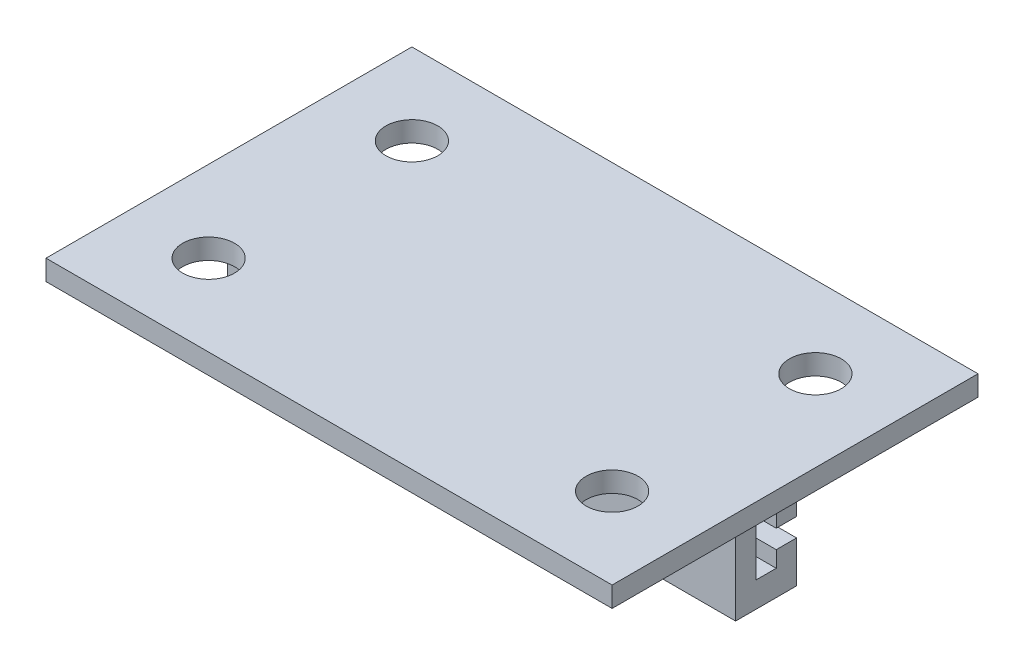
SolidWorks part; units mm, degrees
ref_plane "Front Plane" through (0, 0, 0) normal (0, 0, 1) x (1, 0, 0)
ref_plane "Top Plane" through (0, 0, 0) normal (0, 1, 0) x (1, 0, 0)
ref_plane "Right Plane" through (0, 0, 0) normal (1, 0, 0) x (0, 0, -1)
sketch "Sketch1" plane through (0, 0, 0) normal (1, 0, 0) x (0, 0, -1)
  line L0 (0, 0) -> (6.25, 0)
  line L2 (4, 2.5) -> (2, 2.5)
  line L3 (2, 2.5) -> (2, 7.5)
  line L4 (2, 7.5) -> (4, 7.5)
  line L6 (6.25, 10) -> (0, 10)
  line L7 (0, 10) -> (0, 0)
  line L8 (4, 7.5) -> (4, 5.9125)
  line L9 (4, 5.9125) -> (6, 5.9125)
  line L10 (6, 5.9125) -> (6, 10)
  line L11 (6, 10) -> (6.25, 10)
  line L12 (4, 2.5) -> (4, 4.0875)
  line L13 (4, 4.0875) -> (6, 4.0875)
  line L14 (6, 4.0875) -> (6, 0)
  line L15 (6, 0) -> (6.25, 0)
  dimension "D1" = 5
  dimension "D2" = 1.5875
  dimension "D3" = 2
  dimension "D4" = 2
  dimension "D5" = 2
  dimension "D6" = 10
extrude "Boss-Extrude1" add sketch "Sketch1" along normal blind 50 contours L14 L13 L12 L2 L3 L4 L8 L9 L10 L6 L7 L0
sketch "Sketch2" plane through (0, 10, 0) normal (0, 1, 0) x (1, 0, 0)
  line L1 (-2.85, -15) -> (52.85, -15)
  line L2 (-2.85, -15) -> (-2.85, 21)
  line L3 (-2.85, 21) -> (52.85, 21)
  line L4 (52.85, -15) -> (52.85, 21)
  line L5 (0, 3) -> (50, 3) construction
  line L6 (0, 6) -> (0, 0) construction
  line L7 (50, 6) -> (50, 0) construction
  line L8 (-2.85, 3) -> (52.85, 3) construction
  line L9 (25, 21) -> (25, -15) construction
  line L10 (25, 6) -> (25, 0) construction
  line L11 (50, 6) -> (0, 6) construction
  line L12 (50, 0) -> (0, 0) construction
  line L13 (5.15, -7) -> (44.85, -7) construction
  line L14 (5.15, 13) -> (44.85, 13) construction
  circle A0 centre (5.15, 13) radius 2.55
  circle A1 centre (44.85, 13) radius 2.55
  circle A2 centre (44.85, -7) radius 2.55
  circle A3 centre (5.15, -7) radius 2.55
  dimension "D1" = 5.1
  dimension "D2" = 39.7
  dimension "D3" = 20
  dimension "D4" = 39.7
  dimension "D5" = 8
  dimension "D6" = 8
  dimension "D7" = 8
extrude "Boss-Extrude2" add sketch "Sketch2" along normal blind 2
